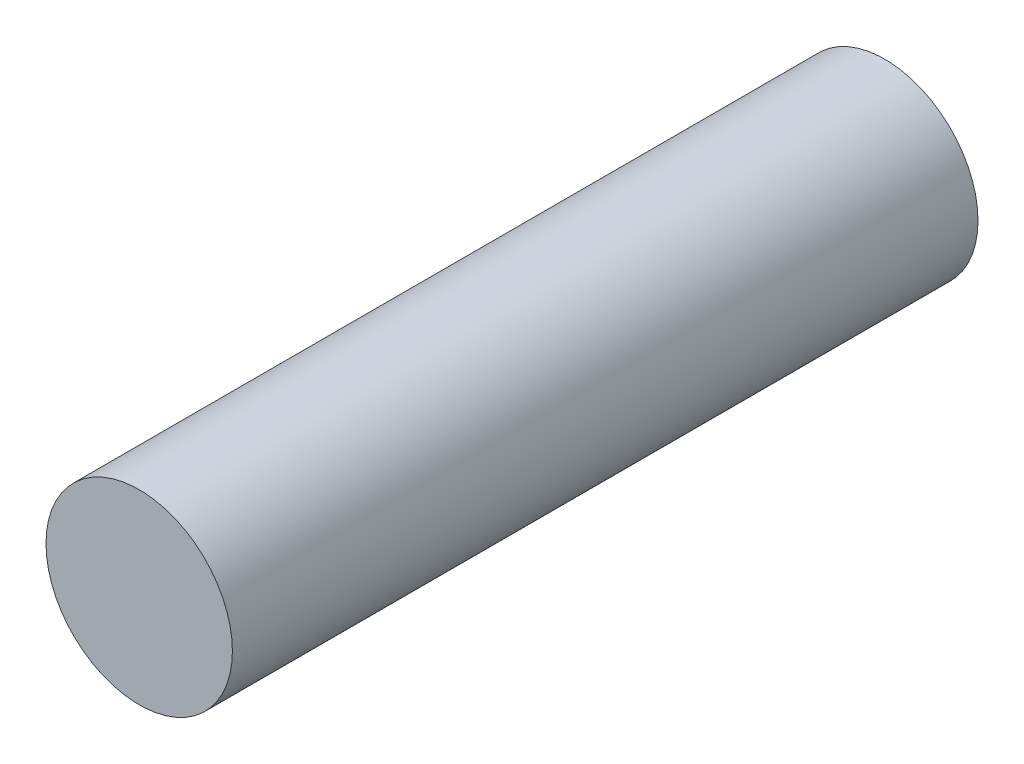
SolidWorks part; units mm, degrees
ref_plane "Front Plane" through (0, 0, 0) normal (0, 0, 1) x (1, 0, 0)
ref_plane "Top Plane" through (0, 0, 0) normal (0, 1, 0) x (1, 0, 0)
ref_plane "Right Plane" through (0, 0, 0) normal (1, 0, 0) x (0, 0, -1)
sketch "Sketch1" plane through (0, 0, 0) normal (0, 0, 1) x (1, 0, 0)
  circle A0 centre (0, 0) radius 500
  dimension "D1" = 1000
extrude "Boss-Extrude1" add sketch "Sketch1" along normal mid plane 4000
